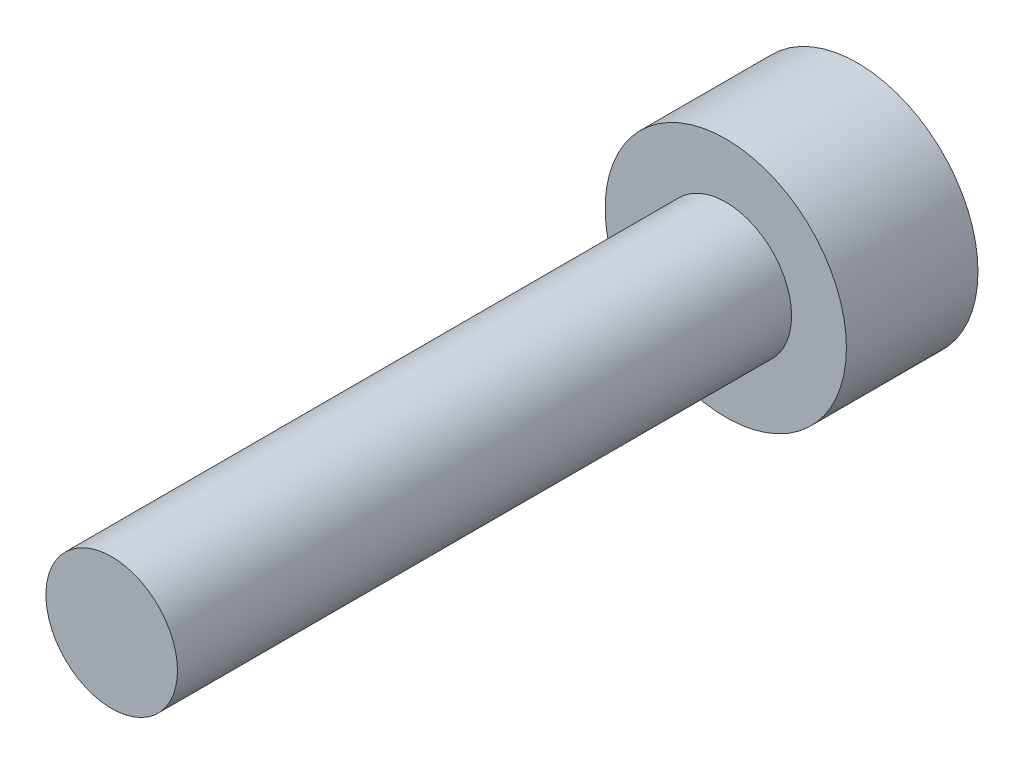
SolidWorks part; units mm, degrees
material "AISI 304"
ref_plane "Alzado" through (0, 0, 0) normal (0, 0, 1) x (1, 0, 0)
ref_plane "Planta" through (0, 0, 0) normal (0, 1, 0) x (1, 0, 0)
ref_plane "Vista lateral" through (0, 0, 0) normal (1, 0, 0) x (0, 0, -1)
sketch "Sk_Cabeza" plane through (0, 0, 0) normal (0, 0, 1) x (1, 0, 0)
  circle A0 centre (0, 0) radius 2.75
  dimension "D1" = 5.5
extrude "Cabeza" add sketch "Sk_Cabeza" along normal blind 3 from offset 3
sketch "Sk_Cuerpo" plane through (0, 0, 0) normal (0, 0, 1) x (1, 0, 0)
  circle A0 centre (0, 0) radius 1.5
  dimension "D1" = 3
extrude "Cuerpo" add sketch "Sk_Cuerpo" along normal blind 14
sketch "Sk_Hexagono_interior" plane through (0, 0, 0) normal (0, 0, 1) x (1, 0, 0)
  line L1 (0, -1.4434) -> (1.25, -0.7217)
  line L2 (1.25, -0.7217) -> (1.25, 0.7217)
  line L3 (1.25, 0.7217) -> (0, 1.4434)
  line L4 (0, 1.4434) -> (-1.25, 0.7217)
  line L5 (-1.25, 0.7217) -> (-1.25, -0.7217)
  line L6 (-1.25, -0.7217) -> (0, -1.4434)
  circle A0 centre (0, 0) radius 1.25 construction
  dimension "D1" = 2.5
extrude "Hexagono_interior" cut sketch "Sk_Hexagono_interior" along normal blind 1.5 from offset 3
